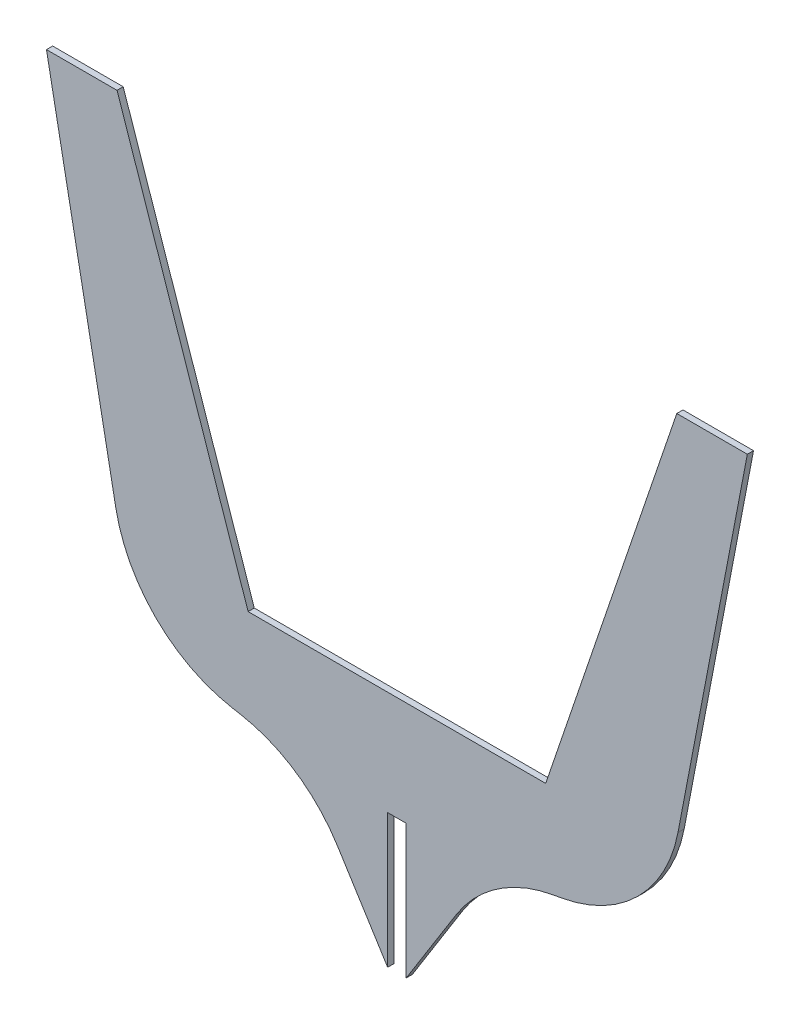
SolidWorks part; units mm, degrees
ref_plane "Plan de face" through (0, 0, 0) normal (0, 0, 1) x (1, 0, 0)
ref_plane "Plan de dessus" through (0, 0, 0) normal (0, 1, 0) x (1, 0, 0)
ref_plane "Plan de droite" through (0, 0, 0) normal (1, 0, 0) x (0, 0, -1)
sketch "Esquisse1" plane through (0, 0, 0) normal (0, 1, 0) x (1, 0, 0)
  point P0 (0, 27.1237)
sketch "Esquisse3" plane through (0, 0, 0) normal (0, 0, 1) x (1, 0, 0)
  line L49 (-52.2777, 1.004) -> (29.8299, -13.9262)
  line L50 (29.8299, -13.9262) -> (70.5528, -78.9262)
  line L51 (70.5528, -78.9262) -> (70.5528, -13.9262)
  line L52 (79.5528, -13.9262) -> (70.5528, -13.9262)
  line L54 (75.0528, -13.9262) -> (75.0528, 36.6646) construction
  line L55 (79.5528, -78.9262) -> (79.5528, -13.9262)
  line L56 (202.3834, 1.004) -> (120.2758, -13.9262)
  line L57 (245.0528, 223.8738) -> (202.3834, 1.004)
  line L61 (210.8251, 223.8738) -> (147.2298, 36.6646)
  line L63 (120.2758, -13.9262) -> (79.5528, -78.9262)
  line L65 (147.2298, 36.6646) -> (2.8759, 36.6646)
  line L66 (210.8251, 223.8738) -> (245.0528, 223.8738)
  line L67 (-60.7194, 223.8738) -> (-94.9472, 223.8738)
  line L68 (-60.7194, 223.8738) -> (2.8759, 36.6646)
  line L69 (-94.9472, 223.8738) -> (-52.2777, 1.004)
  point P2 (173.2999, -9.9307)
  point P3 (186.611, -11.6977)
  point P6 (207.9902, 98.1462)
  point P17 (123.5529, 59.4726)
  point P18 (184.1896, 284.6519)
  point P19 (200.3783, 285.7579)
  point P22 (125.9231, 58.6321)
  point P23 (215.5733, 76.095)
  point P24 (210.8251, 286.0738)
  point P25 (156.3759, 43.3473)
  point P26 (144.3613, -33.2148)
  point P27 (-8.939, -24.0535)
  point P28 (215.2093, 37.0224)
  point P29 (101.6083, -13.9262)
  point P30 (202.3834, 30.304)
  point P31 (147.2298, 36.6646)
  dimension "D2" = 237.8
  dimension "D3" = 340
  dimension "D6" = 9
  dimension "D11" = 65
extrude "Boss.-Extru.3" add sketch "Esquisse3" along normal blind 3
fillet "Congé2" radius 70 4 edges at (29.8299, -13.9262, 1.5) (-52.2777, 1.004, 1.5) (202.3834, 1.004, 1.5) (120.2758, -13.9262, 1.5)
